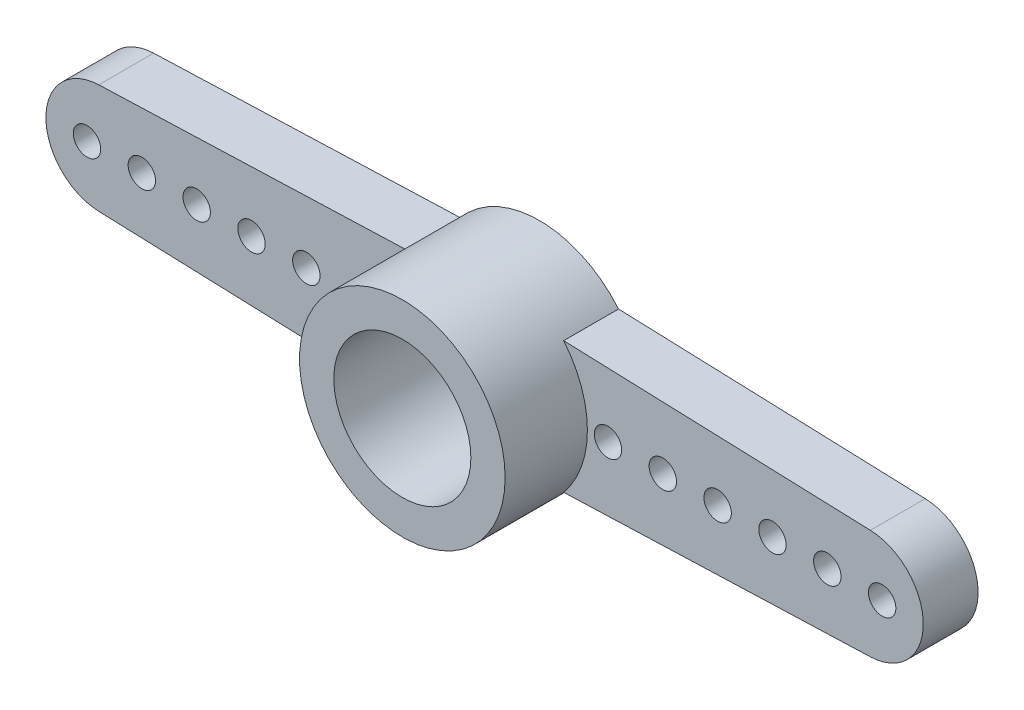
SolidWorks part; units mm, degrees
ref_plane "Спереди" through (0, 0, 0) normal (0, 0, 1) x (1, 0, 0)
ref_plane "Meio" through (0, 0, 0) normal (0, 1, 0) x (1, 0, 0)
ref_plane "Справа" through (0, 0, 0) normal (1, 0, 0) x (0, 0, -1)
sketch "Эскиз1" plane through (0, 0, 0) normal (0, 0, 1) x (1, 0, 0)
  line L0 (0, 0) -> (-14, 0)
  line L1 (-14.0708, 1.9987) -> (0, 2.4974)
  line L2 (-14.0708, -1.9987) -> (0, -2.4974)
  line L4 (14.0708, -1.9987) -> (0, -2.4974)
  line L5 (14.0708, 1.9987) -> (0, 2.4974)
  circle A0 centre (0, 0) radius 3.75
  circle A1 centre (0, 0) radius 2.5
  arc A2 (-13.967, -1.9997) -> (-14.0708, 1.9987) centre (-14, 0) cw
  arc A3 (13.967, -1.9997) -> (14.0708, 1.9987) centre (14, 0) ccw
  dimension "D1" = 7.5
  dimension "D2" = 5
  dimension "D4" = 2
  dimension "D3" = 14
extrude "Бобышка-Вытянуть3" add sketch "Эскиз1" along normal blind 2
sketch "Эскиз2" plane through (0, 0, 2) normal (0, 0, 1) x (1, 0, 0)
  circle A0 centre (0, 0) radius 3.75
  circle A1 centre (0, 0) radius 2.5
  dimension "D1" = 5
extrude "Бобышка-Вытянуть5" add sketch "Эскиз2" along normal blind 3 separate body
sketch "Эскиз3" plane through (0, 0, 2) normal (0, 0, -1) x (-1, 0, 0)
  circle A0 centre (0, 0) radius 3.75
  circle A1 centre (0, 0) radius 2.5
extrude "Бобышка-Вытянуть6" add sketch "Эскиз3" along normal blind 2
sketch "Эскиз4" plane through (0, 0, 0) normal (0, 0, -1) x (-1, 0, 0)
  line L0 (-16, 0) -> (-14.5, 0)
  line L1 (-14.5, 0) -> (-12.5, 0)
  line L2 (-12.5, 0) -> (-10.5, 0)
  line L3 (-10.5, 0) -> (-8.5, 0)
  line L4 (-8.5, 0) -> (-6.5, 0)
  line L5 (-6.5, 0) -> (-4.5, 0)
  arc A0 (-14.0708, 1.9987) -> (-14.0708, -1.9987) centre (-14, 0) ccw construction
  circle A1 centre (-14.5, 0) radius 0.5
  circle A2 centre (-12.5, 0) radius 0.5
  circle A3 centre (-10.5, 0) radius 0.5
  circle A4 centre (-8.5, 0) radius 0.5
  circle A5 centre (-6.5, 0) radius 0.5
  circle A6 centre (-4.5, 0) radius 0.5
  circle A7 centre (4.5, 0) radius 0.5
  circle A8 centre (6.5, 0) radius 0.5
  circle A9 centre (8.5, 0) radius 0.5
  circle A10 centre (10.5, 0) radius 0.5
  circle A11 centre (12.5, 0) radius 0.5
  circle A12 centre (14.5, 0) radius 0.5
  dimension "D2" = 1
  dimension "D8" = 1
  dimension "D9" = 1
  dimension "D10" = 1
  dimension "D11" = 1
  dimension "D12" = 1
  dimension "D1" = 1.5
  dimension "D3" = 2
  dimension "D4" = 2
  dimension "D5" = 2
  dimension "D6" = 2
  dimension "D7" = 2
extrude "Вырез-Вытянуть1" cut sketch "Эскиз4" against normal blind 2
sketch "Эскиз5" plane through (0, 0, 0) normal (0, 0, -1) x (-1, 0, 0)
  circle A0 centre (0, 0) radius 2.5
extrude "Бобышка-Вытянуть7" add sketch "Эскиз5" against normal blind 1
sketch "Эскиз6" plane through (0, 0, 0) normal (0, 0, -1) x (-1, 0, 0)
  circle A0 centre (0, 0) radius 2.5
  dimension "D1" = 5
extrude "Вырез-Вытянуть2" cut sketch "Эскиз6" against normal blind 0.5
sketch "Эскиз7" plane through (0, 0, 0.5) normal (0, 0, -1) x (-1, 0, 0)
  circle A0 centre (0, 0) radius 1.25
  dimension "D1" = 2.5
extrude "Вырез-Вытянуть3" cut sketch "Эскиз7" against normal blind 5
sketch "Эскиз8" plane through (0, 0, 0.5) normal (0, 0, -1) x (-1, 0, 0)
  line L0 (-2.8252, -0.1999) -> (-2.8894, -0.2509)
